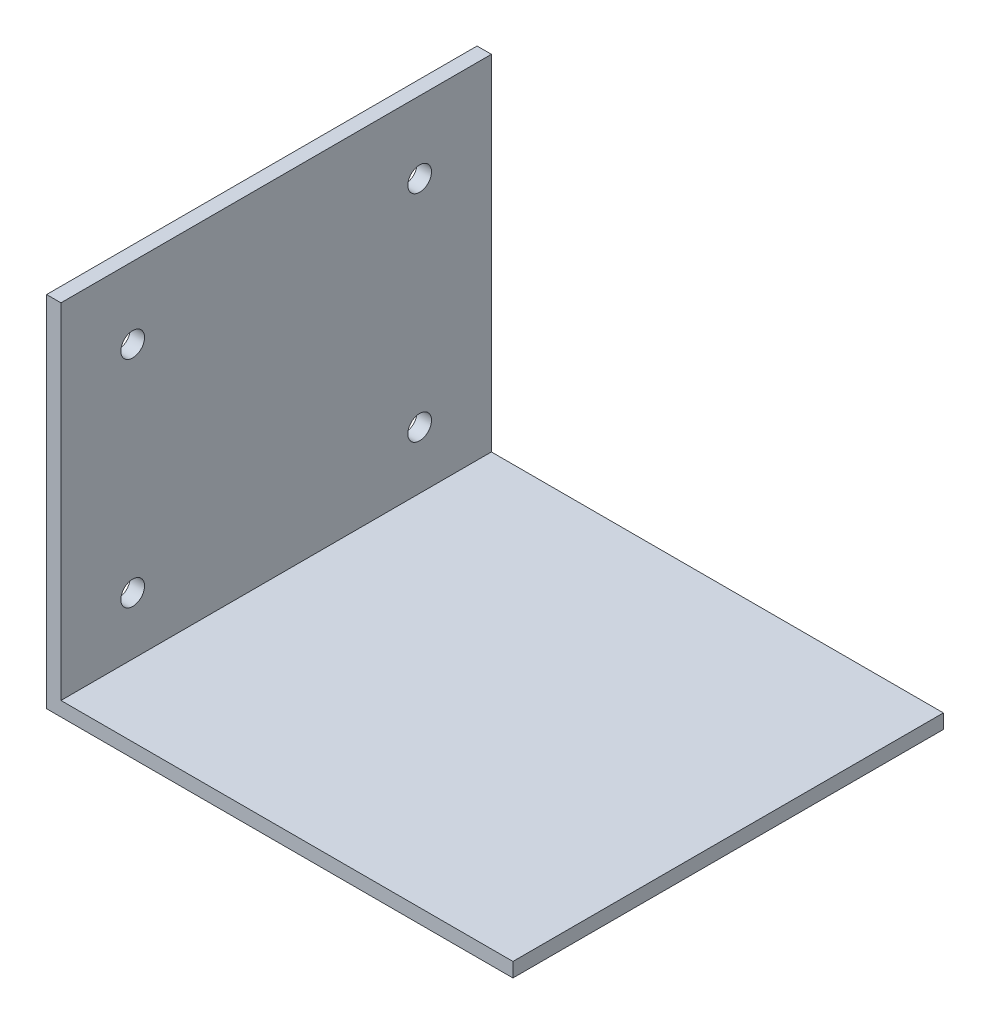
SolidWorks part; units mm, degrees
ref_plane "Front Plane" through (0, 0, 0) normal (0, 0, 1) x (1, 0, 0)
ref_plane "Top Plane" through (0, 0, 0) normal (0, 1, 0) x (1, 0, 0)
ref_plane "Right Plane" through (0, 0, 0) normal (1, 0, 0) x (0, 0, -1)
sketch "Sketch2" plane through (0, 0, 0) normal (0, 0, 1) x (1, 0, 0)
  line L0 (0, 0) -> (0, 100)
  line L1 (0, 100) -> (4, 100)
  line L2 (4, 100) -> (4, 4)
  line L3 (4, 4) -> (130, 4)
  line L4 (130, 4) -> (130, 0)
  line L5 (130, 0) -> (0, 0)
  dimension "D1" = 100
  dimension "D2" = 4
  dimension "D3" = 4
  dimension "D4" = 130
extrude "Boss-Extrude1" add sketch "Sketch2" along normal blind 120
sketch "Sketch4" plane through (4, 0, 0) normal (1, 0, 0) x (0, 0, -1)
  line L0 (0, 4) -> (0, 100) construction
  line L1 (-120, 100) -> (0, 100) construction
  circle A0 centre (-100, 80) radius 3.3
  circle A1 centre (-20, 80) radius 3.3
  circle A2 centre (-20, 20) radius 3.3
  circle A3 centre (-100, 20) radius 3.3
  point P8 (0, 0)
  point P9 (0, 0)
  point P10 (0, 0)
  dimension "D1" = 6.6
  dimension "D2" = 60
  dimension "D3" = 80
  dimension "D4" = 20
  dimension "D5" = 20
extrude "Cut-Extrude1" cut sketch "Sketch4" against normal through all
